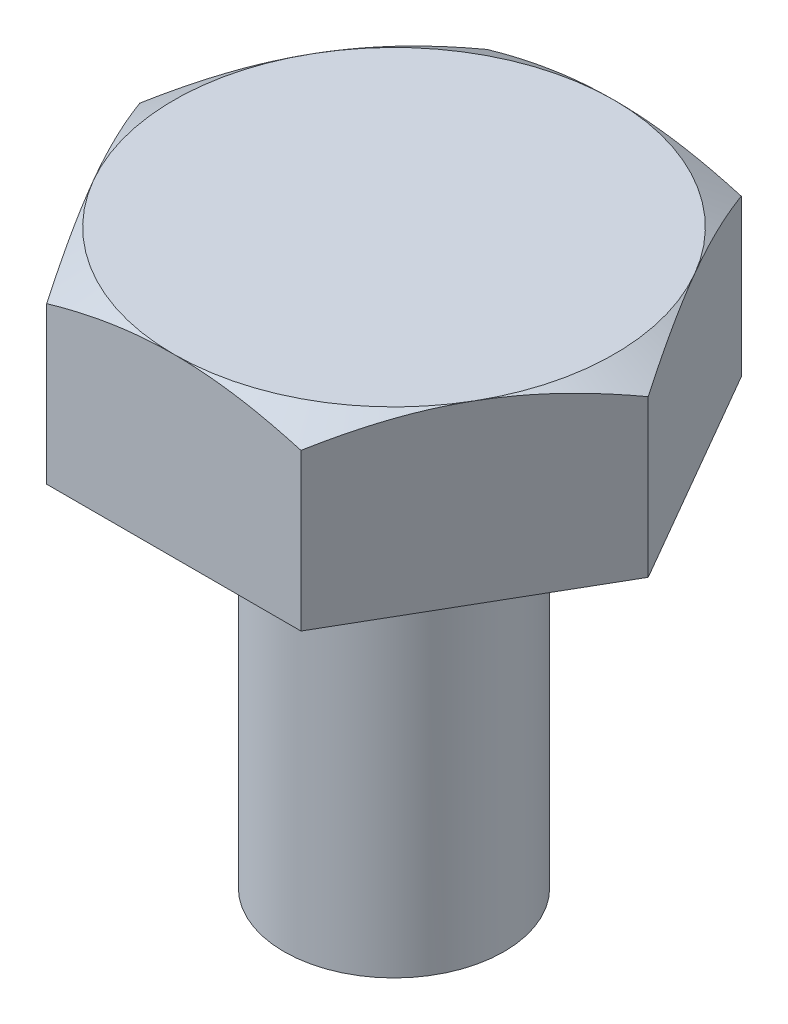
SolidWorks part; units mm, degrees
ref_plane "Front Plane" through (0, 0, 0) normal (0, 0, 1) x (1, 0, 0)
ref_plane "Top Plane" through (0, 0, 0) normal (0, 1, 0) x (1, 0, 0)
ref_plane "Right Plane" through (0, 0, 0) normal (1, 0, 0) x (0, 0, -1)
sketch "Sketch1" plane through (0, 0, 0) normal (0, 1, 0) x (1, 0, 0)
  line L1 (5.7735, 0) -> (2.8868, 5)
  line L2 (2.8868, 5) -> (-2.8868, 5)
  line L3 (-2.8868, 5) -> (-5.7735, 0)
  line L4 (-5.7735, 0) -> (-2.8868, -5)
  line L5 (-2.8868, -5) -> (2.8868, -5)
  line L6 (2.8868, -5) -> (5.7735, 0)
  circle A0 centre (0, 0) radius 5 construction
  dimension "D1" = 10
extrude "Boss-Extrude1" add sketch "Sketch1" against normal blind 4
sketch "Sketch2" plane through (0, 0, 0) normal (0, 1, 0) x (1, 0, 0)
  circle A0 centre (0, 0) radius 5
sketch "Sketch3" plane through (0, 0, 0) normal (0, 0, 1) x (1, 0, 0)
  line L0 (5, 0) -> (5.7735, 0)
  line L1 (5, 0) -> (-5, 0) construction
  line L2 (5.7735, 0) -> (5.7735, -0.4466)
  line L3 (5.7735, -4) -> (5.7735, 0) construction
  line L4 (5.7735, -0.4466) -> (5, 0)
  line L5 (0, 1.337) -> (0, -1.337) construction
  point P15 (0, 0)
  dimension "D1" = 30
revolve "Cut-Revolve1" cut sketch "Sketch3" angle 360 about L5
sketch "Sketch4" plane through (0, -4, 0) normal (0, -1, 0) x (1, 0, 0)
  circle A0 centre (0, 0) radius 2.5
  dimension "D1" = 5
extrude "Boss-Extrude2" add sketch "Sketch4" along normal blind 9
